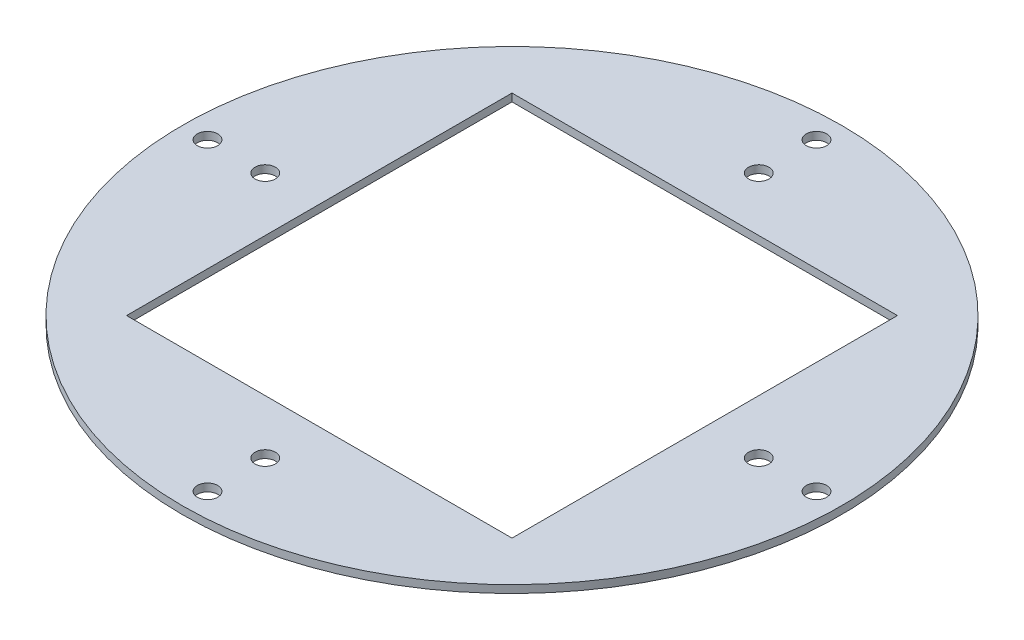
SolidWorks part; units mm, degrees
ref_plane "前视基准面" through (0, 0, 0) normal (0, 0, 1) x (1, 0, 0)
ref_plane "上视基准面" through (0, 0, 0) normal (0, 1, 0) x (1, 0, 0)
ref_plane "右视基准面" through (0, 0, 0) normal (1, 0, 0) x (0, 0, -1)
other "Configuration Table"
sketch "草图1" plane through (0, 0, 0) normal (0, 1, 0) x (1, 0, 0)
  line L0 (0, 85.5) -> (0, 72.5)
  circle A0 centre (0, 0) radius 72.5
  circle A1 centre (0, 0) radius 85.5
  circle A2 centre (0, 79) radius 2.65
  circle A3 centre (79, 0) radius 2.65
  circle A4 centre (0, -79) radius 2.65
  circle A5 centre (-79, 0) radius 2.65
  point P17 (0, 0)
  dimension "D1" = 145
  dimension "D2" = 171
  dimension "D3" = 5.3
  dimension "D4" = 4
extrude "凸台-拉伸1" add sketch "草图1" along normal blind 2
sketch "草图2" plane through (0, 2, 0) normal (0, 1, 0) x (1, 0, 0)
  line L0 (0, 79) -> (0, -79)
  line L2 (-40, -50) -> (40, -50)
  line L3 (-40, -50) -> (-40, 50)
  line L4 (-40, 50) -> (40, 50)
  line L5 (40, -50) -> (40, 50)
  line L6 (-40, -50) -> (40, 50) construction
  line L7 (-40, 50) -> (40, -50) construction
  point P4 (0, 0)
  dimension "D1" = 80
  dimension "D2" = 100
extrude "切除-拉伸2" cut sketch "草图2" against normal blind 2 contours L4 L3 L2 L0 | L2 L5 L4 L0
sketch "草图4" plane through (0, 2, 0) normal (0, 1, 0) x (1, 0, 0)
  circle A0 centre (0, 0) radius 64.0312
  circle A1 centre (0, 64.0312) radius 2.65
  circle A2 centre (64.0312, 0) radius 2.65
  circle A3 centre (0, -64.0312) radius 2.65
  circle A4 centre (-64.0312, 0) radius 2.65
  point P15 (0, 0)
  dimension "D1" = 5.3
  dimension "D2" = 4
extrude "切除-拉伸3" cut sketch "草图4" against normal blind 2 contours A0 A1 | A0 A1 | A4 | A2 | A3
sketch "草图5" plane through (0, 2, 0) normal (0, 1, 0) x (1, 0, 0)
  line L1 (-50, -50) -> (50, -50)
  line L2 (-50, -50) -> (-50, 50)
  line L3 (-50, 50) -> (50, 50)
  line L4 (50, -50) -> (50, 50)
  line L5 (-50, -50) -> (50, 50) construction
  line L6 (-50, 50) -> (50, -50) construction
  point P0 (0, 0)
  dimension "D1" = 100
extrude "切除-拉伸4" cut sketch "草图5" against normal blind 2
